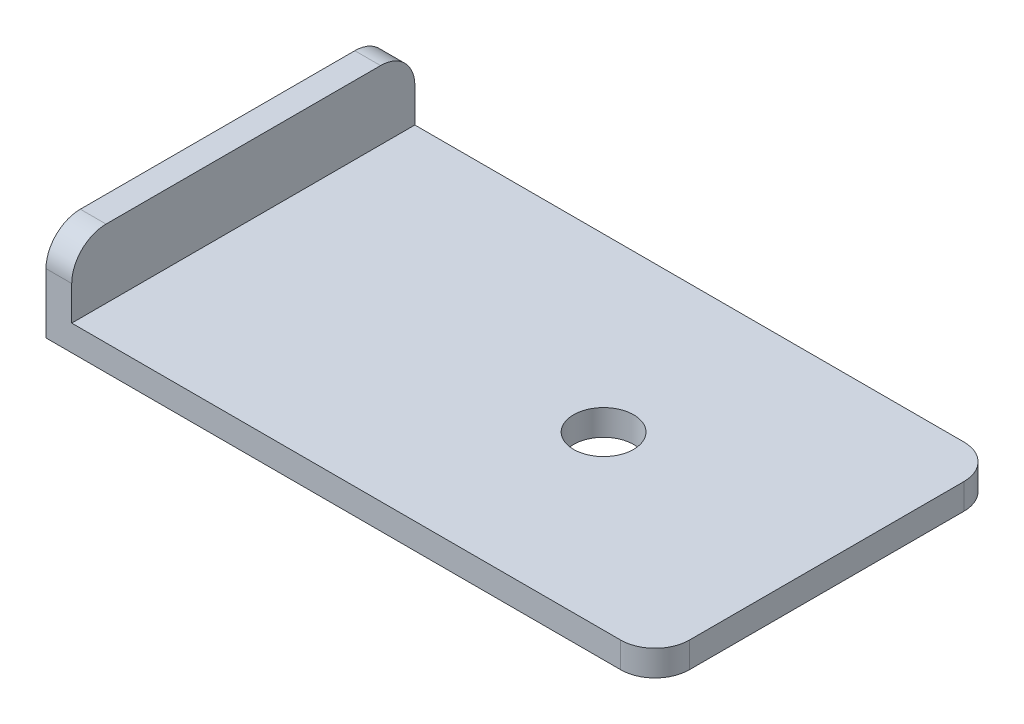
SolidWorks part; units mm, degrees
material "3.0205 (EN-AW 1200)"
ref_plane "Plan de face" through (0, 0, 0) normal (0, 0, 1) x (1, 0, 0)
ref_plane "Plan de dessus" through (0, 0, 0) normal (0, 1, 0) x (1, 0, 0)
ref_plane "Plan de droite" through (0, 0, 0) normal (1, 0, 0) x (0, 0, -1)
sketch "Esquisse1" plane through (0, 0, 0) normal (0, 0, 1) x (1, 0, 0)
  line L0 (0, 19.5) -> (0, 0)
  line L1 (0, 0) -> (35.5, 0)
  dimension "D1" = 19.5
  dimension "D2" = 35.5
extrude "Extru.-Mince1" add sketch "Esquisse1" along normal blind 20 thin thin type one direction reverse wall 1.5
sketch "Esquisse2" plane through (0, 1.5, 0) normal (0, 1, 0) x (1, 0, 0)
  line L0 (35.5, -20) -> (35.5, 0) construction
  line L1 (1.5, -20) -> (1.5, 0) construction
  circle A0 centre (22.5, -10) radius 1.75
  point P4 (35.5, -10)
  dimension "D1" = 21
  dimension "D2" = 3.5
extrude "Enlèv. mat.-Extru.1" cut sketch "Esquisse2" against normal through all
sketch "Esquisse3" plane through (0, 0, 20) normal (0, 0, 1) x (1, 0, 0)
  line L0 (1.5, 19.5) -> (1.5, 1.5) construction
  line L1 (0, 19.5) -> (1.5, 19.5)
  line L2 (0, 19.5) -> (0, 5.5)
  line L3 (0, 5.5) -> (1.5, 5.5)
  line L4 (1.5, 19.5) -> (1.5, 5.5)
  line L5 (1.5, 1.5) -> (35.5, 1.5) construction
  line L6 (0, 0) -> (35.5, 0) construction
  dimension "D1" = 4
  dimension "D2" = 5.5
extrude "Enlèv. mat.-Extru.2" cut sketch "Esquisse3" against normal through all
fillet "Congé1" radius 2 4 edges at (35.5, 0.75, 0) (35.5, 0.75, 20) (0.75, 5.5, 0) (0.75, 5.5, 20)
